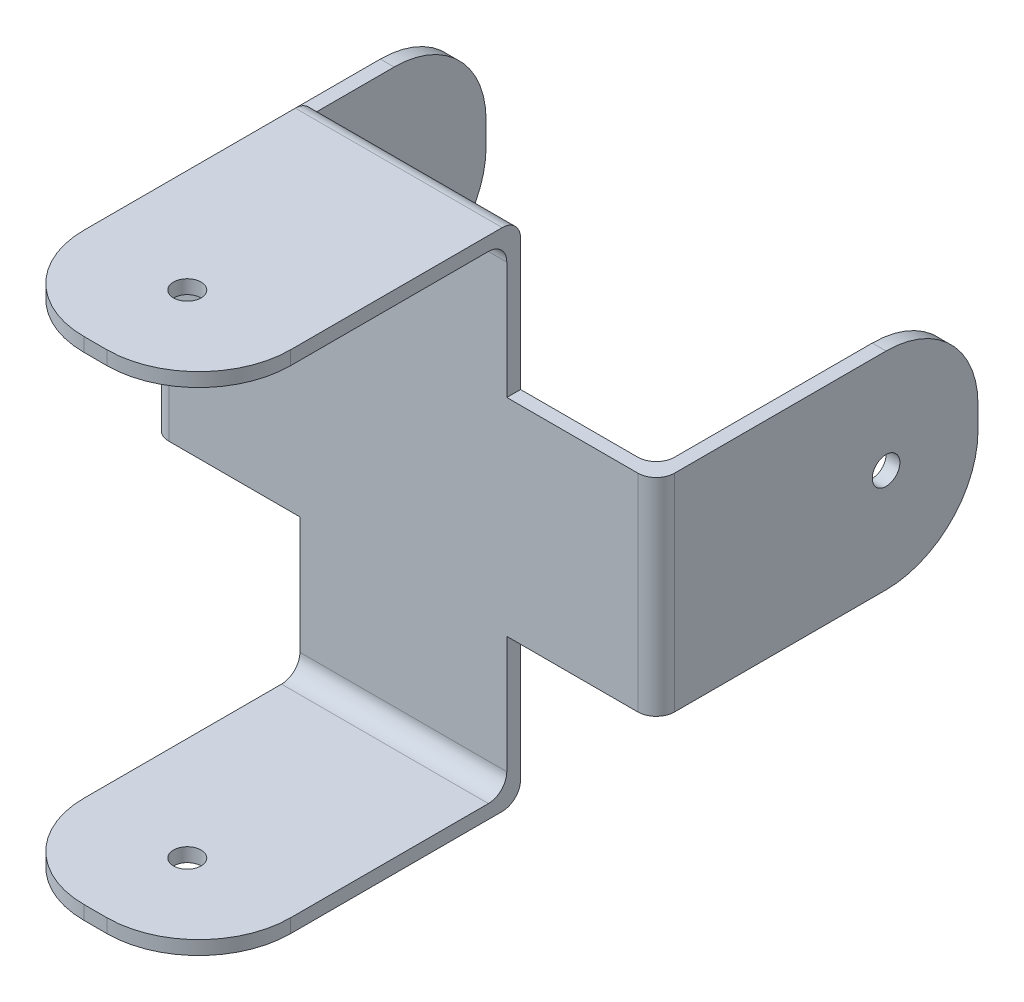
SolidWorks part; units mm, degrees
ref_plane "Front" through (0, 0, 0) normal (0, 0, 1) x (1, 0, 0)
ref_plane "Top" through (0, 0, 0) normal (0, 1, 0) x (1, 0, 0)
ref_plane "Right" through (0, 0, 0) normal (1, 0, 0) x (0, 0, -1)
sketch "草图1" plane through (0, 0, 0) normal (1, 0, 0) x (0, 0, -1)
  line L0 (-35, 27.5) -> (0, 27.5)
  line L1 (0, 27.5) -> (0, -27.5)
  line L2 (0, -27.5) -> (-35, -27.5)
  line L3 (-49.3587, 0) -> (64.7879, 0) construction
  dimension "D1" = 35
  dimension "D2" = 35
  dimension "D3" = 55
extrude "拉伸-薄壁1" add sketch "草图1" along normal mid plane 22.5 thin
sketch "草图2" plane through (0, 27.5, 0) normal (0, 1, 0) x (1, 0, 0)
  line L0 (0, -35) -> (0, 0) construction
  line L1 (11.25, -35) -> (-11.25, -35) construction
  line L2 (11.25, 0) -> (-11.25, 0) construction
  circle A0 centre (0, -25) radius 1.5
  dimension "D1" = 10
  dimension "D2" = 3
extrude "切除-拉伸1" cut sketch "草图2" against normal through all
sketch "草图3" plane through (0, 0, 0) normal (0, 0, -1) x (-1, 0, 0)
  line L1 (27.5, -11.25) -> (-27.5, -11.25)
  line L2 (27.5, -11.25) -> (27.5, 11.25)
  line L3 (27.5, 11.25) -> (-27.5, 11.25)
  line L4 (-27.5, -11.25) -> (-27.5, 11.25)
  line L5 (27.5, -11.25) -> (-27.5, 11.25) construction
  line L6 (27.5, 11.25) -> (-27.5, -11.25) construction
  point P0 (0, 0)
  dimension "D1" = 55
  dimension "D2" = 22.5
extrude "凸台-拉伸1" add sketch "草图3" against normal up to surface (1.5 mm away) up to face at (0, 0, 1.5)
sketch "草图4" plane through (0, 0, 1.5) normal (0, 0, 1) x (1, 0, 0)
  line L0 (27.5, 11.25) -> (11.25, 11.25) construction
  line L1 (27.5, -11.25) -> (26, -11.25)
  line L2 (27.5, -11.25) -> (27.5, 11.25)
  line L3 (27.5, 11.25) -> (26, 11.25)
  line L4 (26, -11.25) -> (26, 11.25)
  line L5 (27.5, -11.25) -> (26, 11.25) construction
  line L6 (27.5, 11.25) -> (26, -11.25) construction
  line L7 (11.25, -11.25) -> (27.5, -11.25) construction
  line L8 (27.5, -11.25) -> (27.5, 11.25) construction
  point P0 (26.75, 0)
  dimension "D1" = 1.5
extrude "凸台-拉伸2" add sketch "草图4" against normal blind 35
mirror "镜向1" about plane through (0, 0, 0) normal (1, 0, 0) of "凸台-拉伸2"
sketch "草图5" plane through (27.5, 0, 0) normal (1, 0, 0) x (0, 0, -1)
  line L0 (33.5, -11.25) -> (33.5, 11.25) construction
  circle A0 centre (23.5, 0) radius 1.5
  dimension "D1" = 3
  dimension "D2" = 10
extrude "切除-拉伸2" cut sketch "草图5" against normal through all
fillet "圆角1" radius 10 8 edges at (11.25, -26.75, 35) (-11.25, -26.75, 35) (-11.25, 26.75, 35) (11.25, 26.75, 35) (-26.75, -11.25, -33.5) (-26.75, 11.25, -33.5) (26.75, -11.25, -33.5) (26.75, 11.25, -33.5)
fillet "圆角2" radius 2 8 edges at (27.5, 0, 1.5) (26, 0, 0) (-27.5, 0, 1.5) (-26, 0, 0) (0, -27.5, 0) (0, -26, 1.5) (0, 26, 1.5) (0, 27.5, 0)
